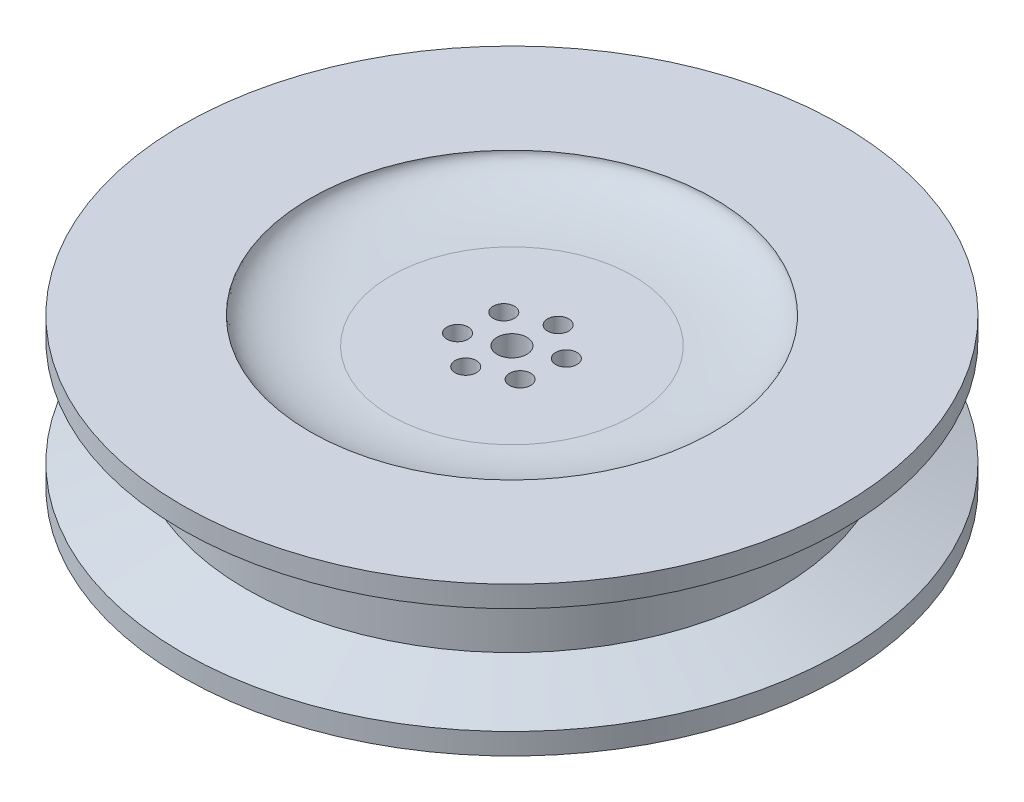
SolidWorks part; units mm, degrees
ref_plane "Front Plane" through (0, 0, 0) normal (0, 0, 1) x (1, 0, 0)
ref_plane "Top Plane" through (0, 0, 0) normal (0, 1, 0) x (1, 0, 0)
ref_plane "Right Plane" through (0, 0, 0) normal (1, 0, 0) x (0, 0, -1)
sketch "Sketch2" plane through (0, 0, 0) normal (0, 0, 1) x (1, 0, 0)
  line L0 (0, 6.2236) -> (0, -4.5788) construction
  line L1 (-1.4, 9.635) -> (-1.4, 0.635)
  line L2 (-1.4, 5.135) -> (-31.5388, 5.135) construction
  line L3 (-25, 2.32) -> (-25, 7.95)
  line L5 (-31, 10.135) -> (-25, 7.95)
  line L6 (-31, 0.135) -> (-25, 2.32)
  line L7 (-31, 10.135) -> (-31, 12.135)
  line L8 (-31, 0.135) -> (-31, -1.865)
  line L9 (-31, 12.135) -> (-19, 12.135)
  line L10 (-31, -1.865) -> (-19, -1.865)
  line L11 (-11.4, 12.135) -> (-11.4, -1.865) construction
  line L14 (-11.4, 9.635) -> (-1.4, 9.635)
  line L18 (-11.4, 0.635) -> (-1.4, 0.635)
  ellipse E0 centre (-11.4, -1.865) end of major axis (-19, -1.865) minor radius 2.5 (-11.4, 0.635) -> (-19, -1.865) ccw
  ellipse E1 centre (-11.4, 12.135) end of major axis (-19, 12.135) minor radius 2.5 (-19, 12.135) -> (-11.4, 9.635) ccw
  point P10 (-25, 5.135)
  point P13 (-31, 5.135)
  dimension "D1" = 1.4
  dimension "D3" = 5.63
  dimension "D4" = 23.6
  dimension "D5" = 10
  dimension "D6" = 2
  dimension "D7" = 2
  dimension "D8" = 12
  dimension "D11" = 10
revolve "Revolve1" add sketch "Sketch2" angle 360 about L0
sketch "Sketch3" plane through (0, 9.635, 0) normal (0, 1, 0) x (1, 0, 0)
  circle A0 centre (-3.115, 2.3466) radius 1
  circle A1 centre (0, 0) radius 1.4 construction
  circle A2 centre (0.4747, 3.871) radius 1
  circle A3 centre (3.5897, 1.5244) radius 1
  circle A4 centre (3.115, -2.3466) radius 1
  circle A5 centre (-0.4747, -3.871) radius 1
  circle A6 centre (-3.5897, -1.5244) radius 1
  point P16 (0, 0)
  dimension "D1" = 3.9
  dimension "D2" = 6
extrude "Cut-Extrude1" cut sketch "Sketch3" against normal blind 10
